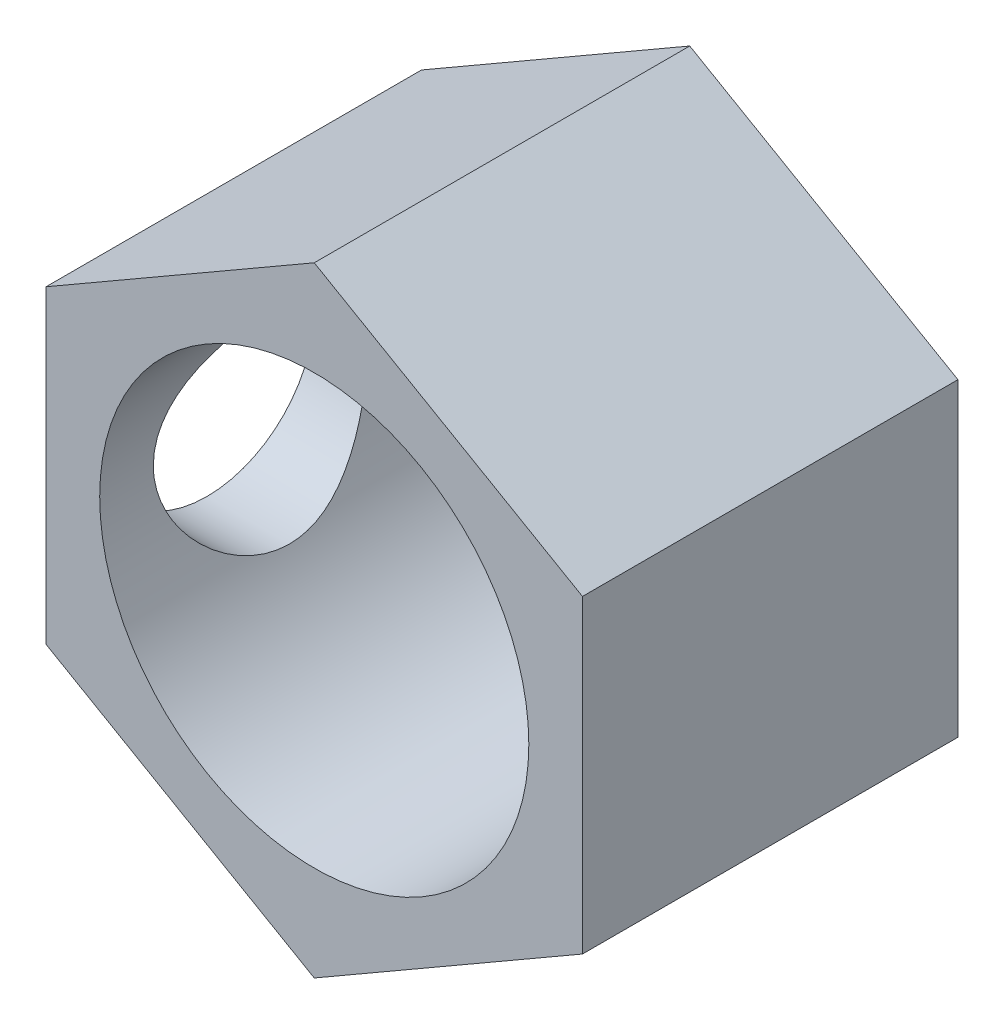
SolidWorks part; units mm, degrees
ref_plane "前视基准面" through (0, 0, 0) normal (0, 0, 1) x (1, 0, 0)
ref_plane "上视基准面" through (0, 0, 0) normal (0, 1, 0) x (1, 0, 0)
ref_plane "右视基准面" through (0, 0, 0) normal (1, 0, 0) x (0, 0, -1)
sketch "Sketch2" plane through (0, 0, 0) normal (0, 0, 1) x (1, 0, 0)
  line L1 (0, -5.7735) -> (5, -2.8868)
  line L2 (5, -2.8868) -> (5, 2.8868)
  line L3 (5, 2.8868) -> (0, 5.7735)
  line L4 (0, 5.7735) -> (-5, 2.8868)
  line L5 (-5, 2.8868) -> (-5, -2.8868)
  line L6 (-5, -2.8868) -> (0, -5.7735)
  circle A0 centre (0, 0) radius 5 construction
extrude "Boss-Extrude1" add sketch "Sketch2" along normal blind 6
sketch "Sketch3" plane through (-5, 0, 0) normal (-1, 0, 0) x (0, 0, 1)
  circle A0 centre (3, 0) radius 2
extrude "Cut-Extrude1" cut sketch "Sketch3" against normal blind 2.5
sketch "Sketch5" plane through (0, 0, 6) normal (0, 0, 1) x (1, 0, 0)
  circle A0 centre (0, 0) radius 2
extrude "Cut-Extrude5" cut sketch "Sketch5" against normal up to next
sketch "Sketch6" plane through (0, 0, 0) normal (0, 0, -1) x (-1, 0, 0)
  line L1 (0, 5.7735) -> (-5, 2.8868)
  line L2 (-5, 2.8868) -> (-5, -2.8868)
  line L3 (-5, -2.8868) -> (0, -5.7735)
  line L4 (0, -5.7735) -> (5, -2.8868)
  line L5 (5, -2.8868) -> (5, 2.8868)
  line L6 (5, 2.8868) -> (0, 5.7735)
  circle A0 centre (0, 0) radius 5 construction
  circle A1 centre (0, 0) radius 2
extrude "Boss-Extrude2" add sketch "Sketch6" along normal blind 1
sketch "Sketch7" plane through (0, 0, -1) normal (0, 0, -1) x (-1, 0, 0)
  circle A0 centre (0, 0) radius 4
extrude "Cut-Extrude6" cut sketch "Sketch7" against normal up to next
